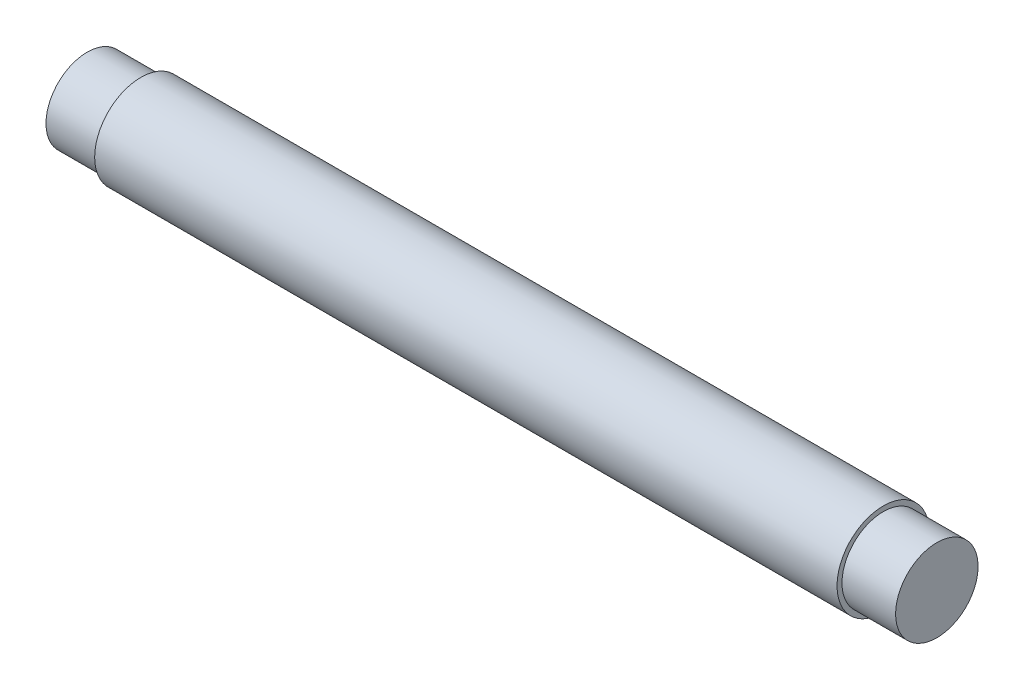
SolidWorks part; units mm, degrees
ref_plane "Face" through (0, 0, 0) normal (0, 0, 1) x (1, 0, 0)
ref_plane "Dessus" through (0, 0, 0) normal (0, 1, 0) x (1, 0, 0)
ref_plane "Droite" through (0, 0, 0) normal (1, 0, 0) x (0, 0, -1)
sketch "Sketch1" plane through (0, 0, 0) normal (0, 0, 1) x (1, 0, 0)
  line L8 (0, 0) -> (50000, 0) construction
  line L9 (-65.405, 0) -> (65.405, 0)
  line L10 (65.405, 0) -> (65.405, 6.35)
  line L11 (65.405, 6.35) -> (57.15, 6.35)
  line L12 (57.15, 6.35) -> (57.15, 7.112)
  line L13 (57.15, 7.112) -> (-57.15, 7.112)
  line L14 (-57.15, 7.112) -> (-57.15, 6.35)
  line L15 (-57.15, 6.35) -> (-65.405, 6.35)
  line L16 (-65.405, 6.35) -> (-65.405, 0)
  point P7 (0, 0)
  dimension "D1" = 12.7
  dimension "D2" = 14.224
  dimension "D3" = 114.3
  dimension "D4" = 8.255
revolve "Revolve1" add sketch "Sketch1" angle 360 about L8
